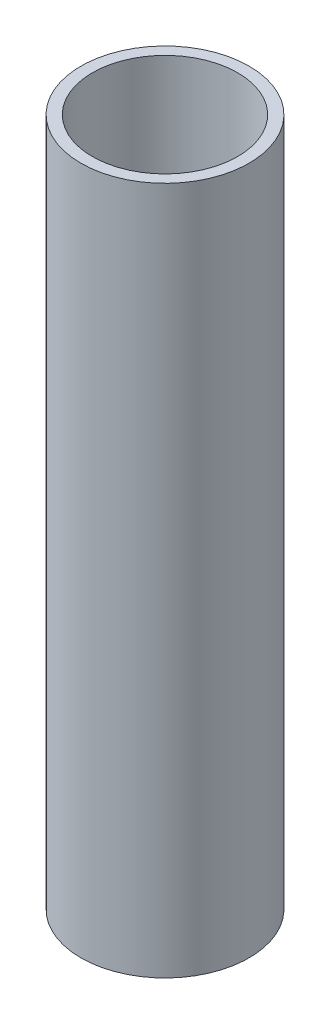
SolidWorks part; units mm, degrees
material "PVC 0.007 Plasticized"
ref_plane "Front Plane" through (0, 0, 0) normal (0, 0, 1) x (1, 0, 0)
ref_plane "Top Plane" through (0, 0, 0) normal (0, 1, 0) x (1, 0, 0)
ref_plane "Right Plane" through (0, 0, 0) normal (1, 0, 0) x (0, 0, -1)
sketch "Sketch1" plane through (0, 0, 0) normal (0, 1, 0) x (1, 0, 0)
  circle A0 centre (0, 0) radius 11
  circle A1 centre (0, 0) radius 9.5
extrude "Boss-Extrude1" add sketch "Sketch1" along normal blind 90
